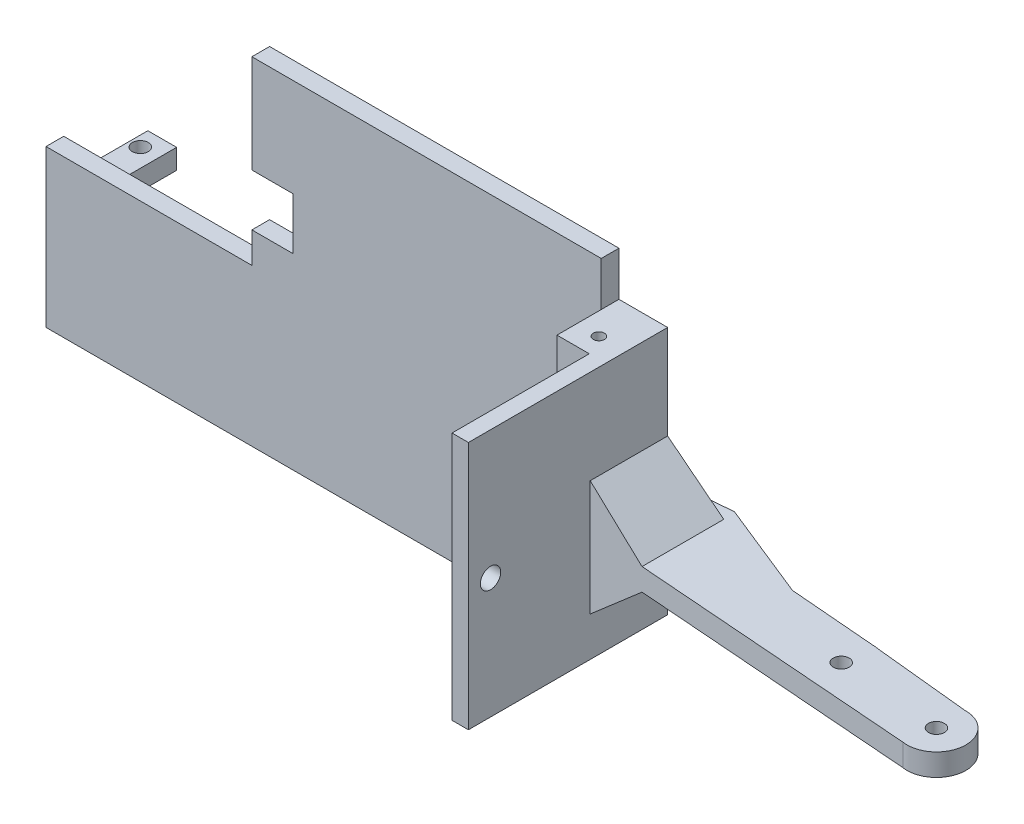
SolidWorks part; units mm, degrees
ref_plane "Front" through (0, 0, 0) normal (0, 0, 1) x (1, 0, 0)
ref_plane "Top" through (0, 0, 0) normal (0, 1, 0) x (1, 0, 0)
ref_plane "Right" through (0, 0, 0) normal (1, 0, 0) x (0, 0, -1)
sketch "Sketch1" plane through (0, 0, 0) normal (0, 1, 0) x (1, 0, 0)
  line L1 (0, 0) -> (78.9, 0)
  line L2 (0, 0) -> (0, 4)
  line L3 (0, 4) -> (78.9, 4)
  line L4 (78.9, 0) -> (78.9, 4)
  line L5 (78.9, 4) -> (88.9, 4)
  line L6 (78.9, 4) -> (78.9, -10)
  line L7 (78.9, -10) -> (88.9, -10)
  line L8 (88.9, 4) -> (88.9, -10)
  dimension "D1" = 4
  dimension "D2" = 10
  dimension "D3" = 88.9
  dimension "D4" = 10
extrude "Boss-Extrude1" add sketch "Sketch1" along normal blind 76.2 contours L1 L4 L3 L2 | L8 L5 L4 L6 L7
sketch "Sketch2" plane through (0, 0, -4) normal (0, 0, -1) x (-1, 0, 0)
  line L1 (0, 0) -> (46.5, 0)
  line L2 (0, 0) -> (0, 26.8941)
  line L3 (0, 26.8941) -> (46.5, 26.8941)
  line L4 (46.5, 0) -> (46.5, 26.8941)
extrude "Boss-Extrude2" add sketch "Sketch2" against normal blind 4
sketch "Sketch5" plane through (0, 0, -4) normal (0, 0, -1) x (-1, 0, 0)
  line L0 (0, 76.2) -> (0, 26.8941) construction
  line L1 (0, 42.3336) -> (-9.286, 42.3336)
  line L2 (0, 42.3336) -> (0, 54.0406)
  line L3 (0, 54.0406) -> (-9.286, 54.0406)
  line L4 (-9.286, 42.3336) -> (-9.286, 54.0406)
extrude "Cut-Extrude2" cut sketch "Sketch5" against normal blind 5
sketch "Sketch6" plane through (0, 0, 0) normal (0, -1, 0) x (-1, 0, 0)
  line L0 (46.5, 4) -> (-88.9, 4) construction
  circle A0 centre (-83.8682, -5.5) radius 1.25
  dimension "D1" = 9.5
extrude "Cut-Extrude3" cut sketch "Sketch6" against normal blind 85
sketch "Sketch7" plane through (0, 0, 0) normal (0, -1, 0) x (1, 0, 0)
  line L0 (78.9, 10) -> (88.9, 10) construction
  line L5 (88.9, -4) -> (78.9, -4)
  line L6 (88.9, -4) -> (88.9, 10)
  line L7 (88.9, 10) -> (78.9, 10)
  line L8 (78.9, -4) -> (78.9, 10)
extrude "Cut-Extrude4" cut sketch "Sketch7" against normal blind 10
sketch "Sketch8" plane through (0, 76.2, 0) normal (0, 1, 0) x (1, 0, 0)
  line L0 (0, 4) -> (88.9, 4) construction
  line L5 (88.9, -10) -> (78.9, -10)
  line L6 (88.9, -10) -> (88.9, 4)
  line L7 (88.9, 4) -> (78.9, 4)
  line L8 (78.9, -10) -> (78.9, 4)
extrude "Cut-Extrude5" cut sketch "Sketch8" against normal blind 10
sketch "Sketch9" plane through (0, 66.2, 0) normal (0, 1, 0) x (1, 0, 0)
  line L0 (88.9, 4) -> (78.9, 4) construction
  line L1 (86.2, 4) -> (89.9, 4)
  line L2 (86.2, 4) -> (86.2, -41)
  line L3 (86.2, -41) -> (89.9, -41)
  line L4 (89.9, 4) -> (89.9, -41)
  line L5 (88.9, -10) -> (88.9, 4) construction
  dimension "D1" = 1
  dimension "D2" = 3.7
  dimension "D3" = 45
extrude "Boss-Extrude4" add sketch "Sketch9" against normal blind 56.2
sketch "Sketch10" plane through (0, 0, 0) normal (0, 0, 1) x (1, 0, 0)
  line L1 (0, 26.8941) -> (-46.5, 26.8941)
  line L2 (0, 26.8941) -> (0, 35.3902)
  line L3 (0, 35.3902) -> (-46.5, 35.3902)
  line L4 (-46.5, 26.8941) -> (-46.5, 35.3902)
extrude "Boss-Extrude5" add sketch "Sketch10" against normal blind 4
sketch "Sketch11" plane through (0, 0, -4) normal (0, 0, -1) x (-1, 0, 0)
  line L0 (-0.3, 26.98) -> (-0.3, 7.02) construction
  line L1 (-0.3, 26.98) -> (-6.9448, 26.98)
  line L2 (-0.3, 26.98) -> (-0.3, 22.4718)
  line L3 (-0.3, 22.4718) -> (-6.9448, 22.4718)
  line L4 (-6.9448, 26.98) -> (-6.9448, 22.4718)
  line L5 (40, 26.98) -> (40, 7.02) construction
  line L6 (40, 22.4718) -> (46.5, 22.4718)
  line L7 (40, 22.4718) -> (40, 26.98)
  line L8 (40, 26.98) -> (46.5, 26.98)
  line L9 (46.5, 22.4718) -> (46.5, 26.98)
  line L10 (46.5, 0) -> (46.5, 35.3902) construction
extrude "Boss-Extrude6" add sketch "Sketch11" along normal blind 19
sketch "Sketch12" plane through (0, 26.98, 0) normal (0, 1, 0) x (1, 0, 0)
  circle A0 centre (-44.15, 18.95) radius 1.8
  circle A1 centre (-44.15, 9.05) radius 1.8
  circle A2 centre (3.85, 18.95) radius 1.8
  circle A3 centre (3.85, 9.05) radius 1.8
extrude "Cut-Extrude6" cut sketch "Sketch12" against normal blind 19
sketch "Sketch14" plane through (89.9, 0, 0) normal (1, 0, 0) x (0, 0, -1)
  line L0 (-41, 66.2) -> (4, 66.2) construction
  line L1 (-41, 10) -> (-41, 66.2) construction
  circle A0 centre (-36, 37.2) radius 2.3
  dimension "D1" = 29
  dimension "D2" = 5
extrude "Cut-Extrude7" cut sketch "Sketch14" against normal blind 10
ref_plane "Plane1" through (0, 35, 0) normal (0, -1, 0) x (-1, 0, 0)
sketch "Sketch15" plane through (0, 35, 0) normal (0, -1, 0) x (-1, 0, 0)
  line L0 (-89.9, 4) -> (-167.3919, -2.7797)
  line L1 (-167.3919, -2.7797) -> (-167.3919, -22.7797)
  line L2 (-167.3919, -22.7797) -> (-89.9, -16)
  line L3 (-89.9, -41) -> (-89.9, 4) construction
  line L4 (-89.9, -16) -> (-89.9, 4)
  circle A0 centre (-167.3919, -12.7797) radius 10
  dimension "D1" = 95
  dimension "D2" = 20
extrude "Boss-Extrude7" add sketch "Sketch15" along normal blind 5 contours A0 L2 L4 L0 | L2 A0 L1 | L1 A0
sketch "Sketch16" plane through (0, 35, 0) normal (0, 1, 0) x (1, 0, 0)
  line L0 (89.9, 4) -> (167.3919, -2.7797) construction
  circle A0 centre (167.3919, -12.7797) radius 1.8
  circle A1 centre (143.8565, -10.7588) radius 1.8
  dimension "D1" = 23.622
  dimension "D2" = 10
extrude "Cut-Extrude8" cut sketch "Sketch16" against normal blind 10
sketch "Sketch17" plane through (0, 0, -4) normal (0, 0, -1) x (-1, 0, 0)
  line L0 (-89.9, 44.9691) -> (-102.5702, 35)
  line L1 (-89.9, 35) -> (-89.9, 66.2) construction
  line L2 (-89.9, 35) -> (-167.3919, 35) construction
  line L3 (-102.5702, 35) -> (-102.5702, 30)
  line L4 (-89.9, 30) -> (-167.3919, 30) construction
  line L5 (-102.5702, 30) -> (-89.9, 18.8968)
  line L6 (-89.9, 10) -> (-89.9, 30) construction
  line L7 (-89.9, 18.8968) -> (-89.9, 44.9691)
extrude "Boss-Extrude8" add sketch "Sketch17" against normal blind 21
sketch "Sketch18" plane through (0, 35, 0) normal (0, 1, 0) x (1, 0, 0)
  line L0 (68.1556, 4) -> (102.3106, 6.6892)
  line L1 (0, 4) -> (78.9, 4) construction
  line L2 (102.3106, 6.6892) -> (114.2799, 1.867)
  line L3 (102.5702, 2.8915) -> (167.3919, -2.7797) construction
  line L4 (114.2799, 1.867) -> (68.1556, 4)
extrude "Boss-Extrude9" add sketch "Sketch18" against normal blind 5
sketch "Sketch19" plane through (0, 35, 0) normal (0, 1, 0) x (1, 0, 0)
  line L0 (114.2799, 1.867) -> (124.2244, -2.1394)
  line L1 (143.8565, -3.7588) -> (124.2244, -2.1394)
  line L2 (143.8565, -3.7588) -> (168.8672, -6.305)
  line L3 (102.4154, -17.095) -> (144.8117, -17.6933)
  line L4 (167.3919, -22.7797) -> (101.3301, -17) construction
  line L5 (144.8117, -17.6933) -> (167.3919, -19.4203)
  circle A0 centre (167.3919, -12.7797) radius 6.6406
  circle A1 centre (143.8565, -10.7588) radius 7
extrude "Cut-Extrude9" cut sketch "Sketch19" against normal blind 5
sketch "Sketch21" plane through (0, 35, 0) normal (0, 1, 0) x (1, 0, 0)
  line L0 (148.9651, -18.011) -> (89.9, -13.4936)
  line L1 (144.8117, -17.6933) -> (166.382, -19.343) construction
  line L2 (89.9, -41) -> (89.9, 4) construction
  line L3 (89.9, -13.4936) -> (89.9, -22.398)
  line L4 (89.9, -22.398) -> (148.9651, -18.011)
extrude "Cut-Extrude10" cut sketch "Sketch21" against normal blind 25 and the other way blind 25
